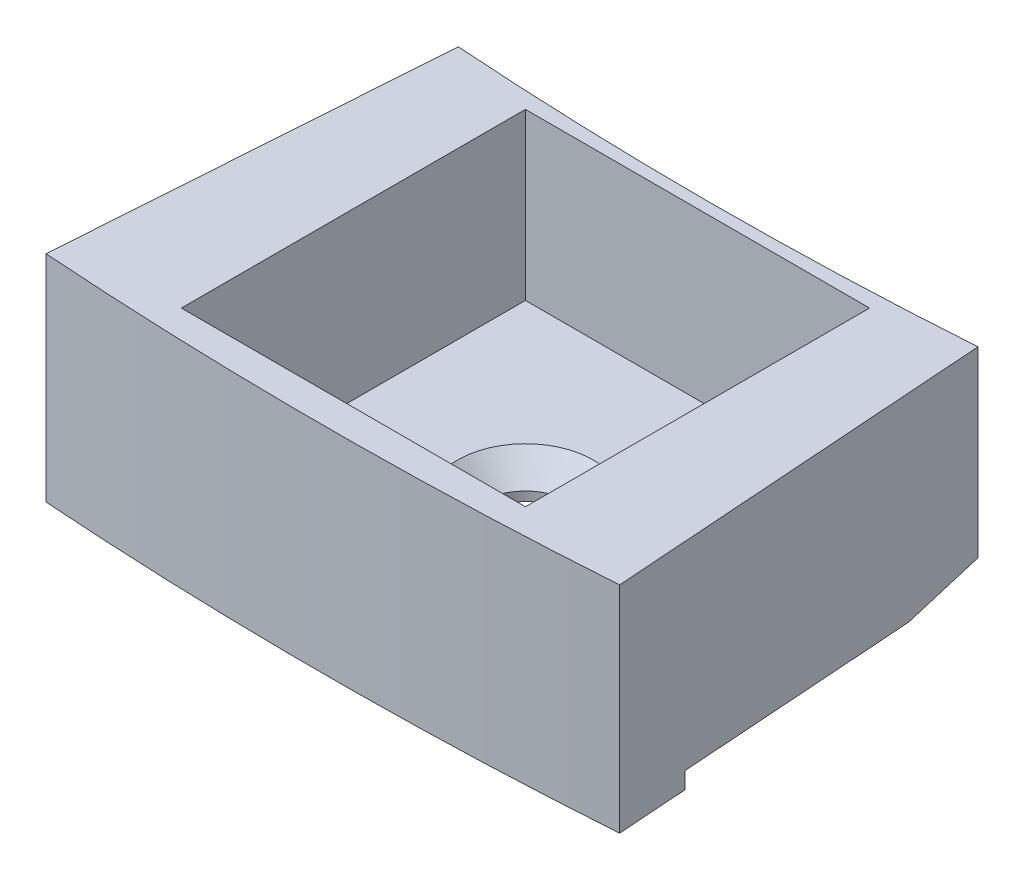
SolidWorks part; units mm, degrees
ref_plane "Front Plane" through (0, 0, 0) normal (0, 0, 1) x (1, 0, 0)
ref_plane "Top Plane" through (0, 0, 0) normal (0, 1, 0) x (1, 0, 0)
ref_plane "Right Plane" through (0, 0, 0) normal (1, 0, 0) x (0, 0, -1)
sketch "BASE" plane through (0, 0, 0) normal (0, 1, 0) x (1, 0, 0)
  line L0 (0, 0) -> (0, -243.5) construction
  line L1 (15.9742, -228.4422) -> (16.9857, -242.9068)
  line L2 (-15.9742, -228.4422) -> (-16.9857, -242.9068)
  line L3 (0, 0) -> (15.9742, -228.4422) construction
  line L4 (0, 0) -> (-15.9742, -228.4422) construction
  line L5 (0, -229) -> (0, -243.5) construction
  line L7 (-10, -226.25) -> (10, -226.25) construction
  line L8 (-10, -226.25) -> (-10, -246.25) construction
  line L9 (-10, -246.25) -> (10, -246.25) construction
  line L10 (10, -226.25) -> (10, -246.25) construction
  line L11 (-10, -226.25) -> (10, -246.25) construction
  line L12 (-10, -246.25) -> (10, -226.25) construction
  arc A0 (-16.9857, -242.9068) -> (16.9857, -242.9068) centre (0, 0) ccw
  arc A1 (-15.9742, -228.4422) -> (15.9742, -228.4422) centre (0, 0) ccw
  circle A2 centre (0, -236.25) radius 2.65
  dimension "D1" = 487
  dimension "D2" = 14.5
  dimension "D6" = 5.3
  dimension "D3" = 4
  dimension "D4" = 4
  dimension "D5" = 20
sketch "Sketch2" plane through (0, 0, 0) normal (0, 1, 0) x (1, 0, 0)
  line L1 (-15.9742, -228.4422) -> (-16.9857, -242.9068) construction
  line L3 (15.9742, -228.4422) -> (16.9857, -242.9068) construction
  line L4 (0, 0) -> (-17.3345, -247.8947) construction
  line L5 (0, 0) -> (17.3345, -247.8947) construction
  line L6 (-15.9847, -228.5918) -> (-17.3345, -247.8947)
  line L7 (15.9847, -228.5918) -> (17.3345, -247.8947)
  arc A0 (15.9847, -228.5918) -> (-15.9847, -228.5918) centre (0, 0) cw
  arc A1 (-15.9742, -228.4422) -> (15.9742, -228.4422) centre (0, 0) ccw construction
  arc A2 (17.3345, -247.8947) -> (-17.3345, -247.8947) centre (0, 0) cw
  arc A3 (-16.9857, -242.9068) -> (16.9857, -242.9068) centre (0, 0) ccw construction
  circle A4 centre (0, -236.25) radius 2.65
  dimension "D1" = 0.15
  dimension "D2" = 5
  dimension "D3" = 5.3
extrude "Boss-Extrude1" add sketch "Sketch2" along normal blind 2
sketch "Sketch3" plane through (0, 0, 0) normal (0, 1, 0) x (1, 0, 0)
  line L0 (0, 0) -> (15.9742, -228.4422) construction
  line L1 (0, 0) -> (-15.9742, -228.4422) construction
  line L2 (-15.7057, -224.6015) -> (-15.9847, -228.5918)
  line L3 (15.7057, -224.6015) -> (15.9847, -228.5918)
  arc A0 (15.9847, -228.5918) -> (-15.9847, -228.5918) centre (0, 0) cw
  arc A1 (15.7057, -224.6015) -> (-15.7057, -224.6015) centre (0, 0) cw
  dimension "D1" = 4
extrude "Boss-Extrude2" add sketch "Sketch3" against normal blind 2 from surface at 2 starting at face at (0, 2, 238.5341)
chamfer "Chamfer1" distance 4.5 angle 12 1 edges at (0, 0, 225.15)
sketch "Sketch4" plane through (0, 0, 0) normal (0, -1, 0) x (1, 0, 0)
  line L0 (15.9742, 228.4422) -> (16.9857, 242.9068) construction
  line L1 (-16.0196, 229.0906) -> (-17.3345, 247.8947) construction
  line L2 (17.3345, 247.8947) -> (16.0196, 229.0906) construction
  line L3 (-17.3345, 247.8947) -> (-17.038, 243.655)
  line L4 (17.3345, 247.8947) -> (17.038, 243.655)
  arc A0 (-17.038, 243.655) -> (17.038, 243.655) centre (0, 0) cw
  arc A1 (-17.3345, 247.8947) -> (17.3345, 247.8947) centre (0, 0) cw
  arc A2 (16.9857, 242.9068) -> (-16.9857, 242.9068) centre (0, 0) ccw construction
  arc A3 (17.3345, 247.8947) -> (-17.3345, 247.8947) centre (0, 0) ccw construction
  dimension "D2" = 0.75
extrude "Boss-Extrude3" add sketch "Sketch4" along normal blind 1
sketch "Sketch18" plane through (0, 2, 0) normal (0, 1, 0) x (1, 0, 0)
  circle A0 centre (0, -236.25) radius 4.225
  dimension "D1" = 8.45
hole_wizard "CSK for M3.5 Flat Head Machine Screw2" positions "Sketch19" profile "Sketch20" countersink size "M3.5" standard "ANSI Metric" end condition up to next
sketch "Sketch19" plane through (0, 2, 0) normal (0, 1, 0) x (1, 0, 0)
  point P0 (0, -236.25)
sketch "Sketch20" plane through (0, 2, 236.25) normal (1, 0, 0) x (0, 0, 1)
  line L0 (0, 0) -> (0, 3)
  line L1 (0, 3) -> (1.85, 3)
  line L2 (1.85, 3) -> (1.85, 2.25)
  line L3 (1.85, 2.25) -> (4.1, 0)
  line L5 (4.1, 0) -> (0, 0)
  line L6 (-1.85, 2.25) -> (-4.1, 0) construction
  line L11 (0, -6.35) -> (0, 107.95) construction
  dimension "Thru Hole Dia." = 3.7
  dimension "Thru Hole Depth" = 3
  dimension "Near C'Sink Dia." = 8.2
  dimension "Near C'Sink Angle" = 90
sketch "Sketch21" plane through (0, 2, 0) normal (0, 1, 0) x (1, 0, 0)
  line L0 (-10, -226.25) -> (10, -246.25) construction
  line L1 (-10, -226.25) -> (10, -226.25) construction
  line L2 (-10, -226.25) -> (-10, -246.25) construction
  line L3 (-10, -246.25) -> (10, -246.25) construction
  line L4 (10, -226.25) -> (10, -246.25) construction
  line L5 (-10, -226.25) -> (10, -246.25) construction
  line L6 (-10, -246.25) -> (10, -226.25) construction
  line L8 (-10.4, -225.85) -> (10.4, -225.85)
  line L9 (-10.4, -225.85) -> (-10.4, -246.65)
  line L10 (-10.4, -246.65) -> (10.4, -246.65)
  line L11 (10.4, -225.85) -> (10.4, -246.65)
  line L12 (-10.4, -225.85) -> (10.4, -246.65) construction
  line L13 (-10.4, -246.65) -> (10.4, -225.85) construction
  line L15 (17.3345, -247.8947) -> (15.7057, -224.6015)
  line L16 (-15.7057, -224.6015) -> (-17.3345, -247.8947)
  line L17 (17.3345, -247.8947) -> (15.7057, -224.6015)
  line L18 (-15.7057, -224.6015) -> (-17.3345, -247.8947)
  arc A2 (-15.7057, -224.6015) -> (15.7057, -224.6015) centre (0, 0) ccw
  arc A3 (-17.3345, -247.8947) -> (17.3345, -247.8947) centre (0, 0) ccw
  arc A4 (-15.7057, -224.6015) -> (15.7057, -224.6015) centre (0, 0) ccw
  arc A5 (-17.3345, -247.8947) -> (17.3345, -247.8947) centre (0, 0) ccw
  point P0 (0, -236.25)
  point P8 (0, -236.25)
  dimension "D1" = 20
  dimension "D2" = 0.4
  dimension "D3" = 0.4
  dimension "D4" = 0
extrude "Boss-Extrude4" add sketch "Sketch21" along normal blind 10
